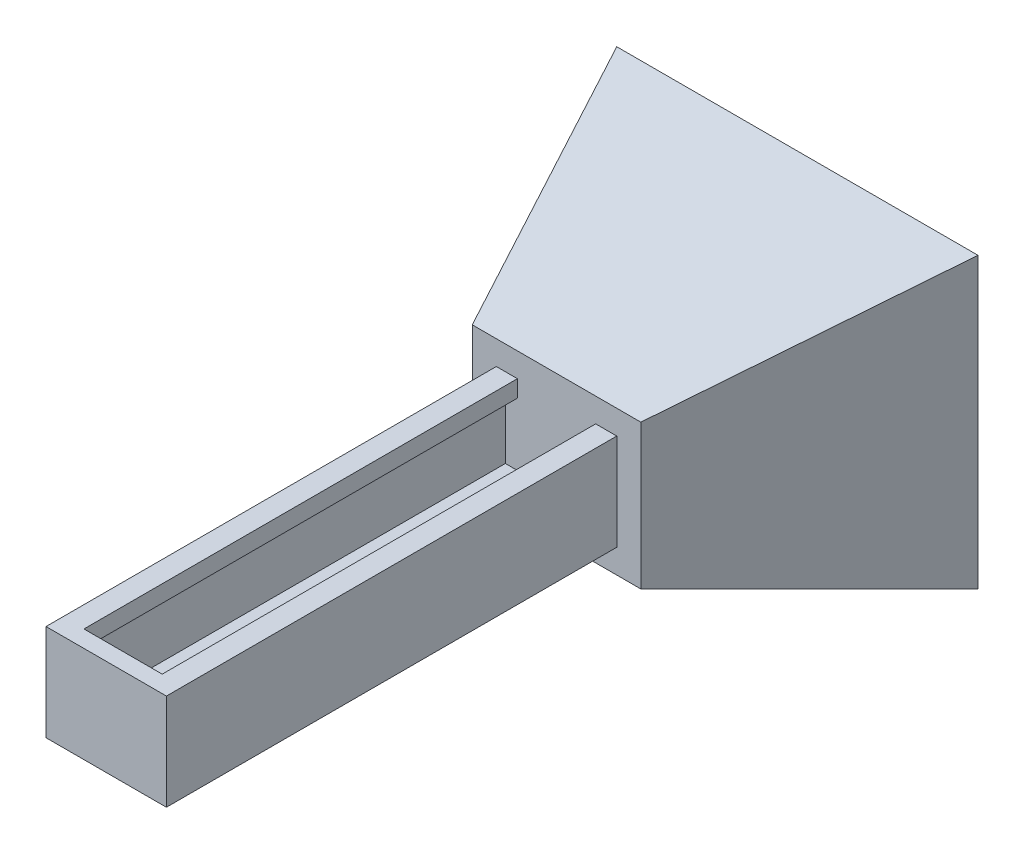
SolidWorks part; units mm, degrees
ref_plane "Front Plane" through (0, 0, 0) normal (0, 0, 1) x (1, 0, 0)
ref_plane "Top Plane" through (0, 0, 0) normal (0, 1, 0) x (1, 0, 0)
ref_plane "Right Plane" through (0, 0, 0) normal (1, 0, 0) x (0, 0, -1)
sketch "Sketch2" plane through (0, 0, 0) normal (0, 0, 1) x (1, 0, 0)
  line L1 (375, -300) -> (-375, -300)
  line L2 (375, -300) -> (375, 300)
  line L3 (375, 300) -> (-375, 300)
  line L4 (-375, -300) -> (-375, 300)
  line L5 (375, -300) -> (-375, 300) construction
  line L6 (375, 300) -> (-375, -300) construction
  point P0 (0, 0)
  dimension "D1" = 750
  dimension "D2" = 600
extrude "Boss-Extrude1" add sketch "Sketch2" against normal blind 500
sketch "Sketch3" plane through (0, -300, 0) normal (0, -1, 0) x (1, 0, 0)
  line L7 (-375, -500) -> (-375, 0)
  line L8 (-375, 0) -> (-175, 0)
  line L9 (-375, 0) -> (375, 0) construction
  line L10 (-175, 0) -> (-375, -500)
  line L11 (375, 0) -> (175, 0)
  line L12 (175, 0) -> (375, -500)
  line L13 (375, -500) -> (375, 0)
  line L14 (375, -500) -> (375, 0) construction
  dimension "D1" = 200
  dimension "D2" = 200
sketch "Sketch4" plane through (375, 0, 0) normal (1, 0, 0) x (0, 0, -1)
  line L0 (500, -300) -> (0, -300)
  line L1 (500, -300) -> (0, -300) construction
  line L2 (500, -300) -> (500, 300) construction
  line L3 (0, -300) -> (0, -150)
  line L4 (0, -300) -> (0, 300) construction
  line L5 (0, -150) -> (500, -300)
  line L6 (0, 300) -> (0, 150)
  line L7 (0, 150) -> (500, 300)
  line L8 (500, 300) -> (0, 300)
  dimension "D1" = 150
  dimension "D2" = 150
extrude "Cut-Extrude2" cut sketch "Sketch3" against normal through all
extrude "Cut-Extrude3" cut sketch "Sketch4" against normal through all
sketch "Sketch5" plane through (0, 0, 0) normal (0, 0, 1) x (1, 0, 0)
  line L0 (-81.25, 100) -> (-81.25, 65)
  line L1 (125, -100) -> (-125, -100)
  line L2 (125, -100) -> (125, 100)
  line L3 (125, 100) -> (-125, 100)
  line L4 (-125, -100) -> (-125, 100)
  line L5 (125, -100) -> (-125, 100) construction
  line L6 (125, 100) -> (-125, -100) construction
  line L7 (-81.25, 65) -> (-106.25, 65)
  line L8 (-106.25, 65) -> (-106.25, -65)
  line L9 (-106.25, -65) -> (-81.25, -65)
  line L10 (-81.25, -65) -> (81.25, -65)
  line L11 (-81.25, -100) -> (81.25, -100)
  line L13 (81.25, -65) -> (106.25, -65)
  line L14 (106.25, -65) -> (106.25, 65)
  line L15 (106.25, 65) -> (81.25, 65)
  line L16 (81.25, 65) -> (81.25, 100)
  point P0 (0, 0)
  dimension "D1" = 250
  dimension "D2" = 200
  dimension "D3" = 35
  dimension "D4" = 25
extrude "Boss-Extrude2" add sketch "Sketch5" along normal blind 900 contours L16 L15 L14 L13 L10 L9 L8 L7 L0 L3 L4 L1 L2
sketch "Sketch6" plane through (125, 0, 0) normal (1, 0, 0) x (0, 0, -1)
  line L0 (-900, -100) -> (-900, 100) construction
  line L1 (-900, -100) -> (-935, -100)
  line L2 (-900, -100) -> (-900, 100)
  line L3 (-900, 100) -> (-935, 100)
  line L4 (-935, -100) -> (-935, 100)
  dimension "D1" = 35
extrude "Boss-Extrude3" add sketch "Sketch6" against normal up to surface (250 mm away) up to face at (-125, 0, 450)
sketch "Sketch8" plane through (0, 0, 0) normal (1, 0, 0) x (0, 0, -1)
  line L0 (-150, 0) -> (-750, 0) construction
  line L2 (-150, 0) -> (-750, 0)
  dimension "D1" = 600
  dimension "D2" = 150
